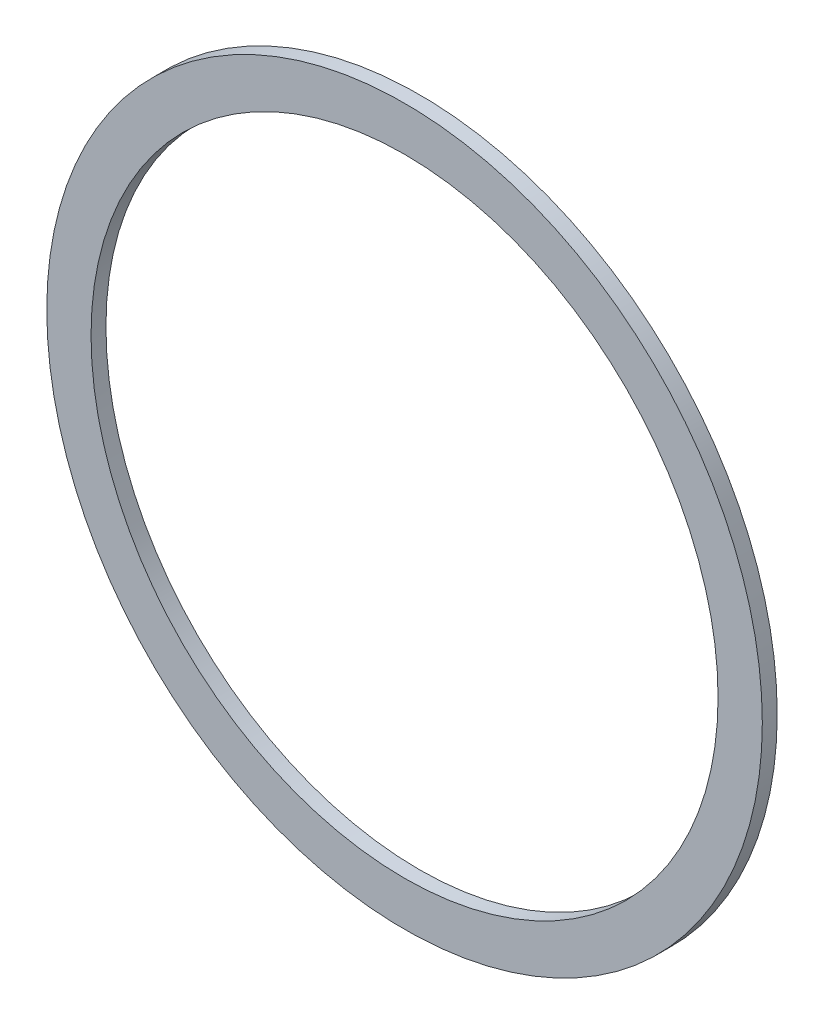
SolidWorks part; units mm, degrees
ref_plane "Plane1" through (0, 0, 0) normal (0, 0, 1) x (1, 0, 0)
ref_plane "Plane2" through (0, 0, 0) normal (0, 1, 0) x (1, 0, 0)
ref_plane "Plane3" through (0, 0, 0) normal (1, 0, 0) x (0, 0, -1)
other "Configuration Table"
sketch "Sketch1" plane through (0, 0, 0) normal (0, 0, 1) x (1, 0, 0)
  circle A0 centre (0, 0) radius 539.75
  circle A1 centre (0, 0) radius 615.95
  dimension "D1" = 1079.5
  dimension "D2" = 1231.9
extrude "Base-Extrude" add sketch "Sketch1" against normal blind 25.654
